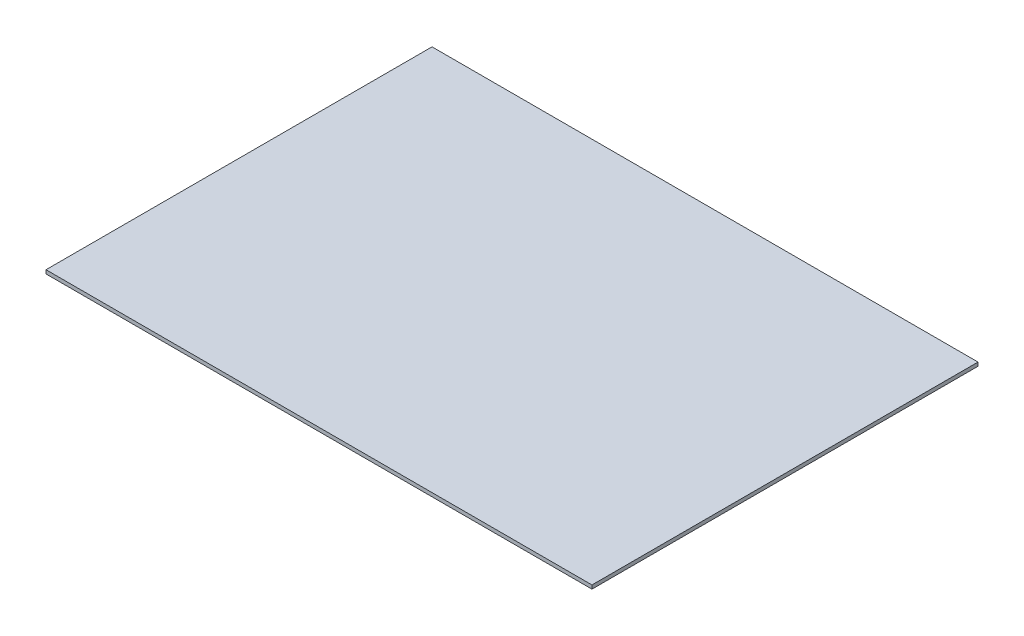
SolidWorks part; units mm, degrees
ref_plane "Plan de face" through (0, 0, 0) normal (0, 0, 1) x (1, 0, 0)
ref_plane "Plan de dessus" through (0, 0, 0) normal (0, 1, 0) x (1, 0, 0)
ref_plane "Plan de droite" through (0, 0, 0) normal (1, 0, 0) x (0, 0, -1)
sketch "Esquisse1" plane through (0, 0, 0) normal (0, 1, 0) x (1, 0, 0)
  line L1 (0, 0) -> (-297, 0)
  line L2 (0, 0) -> (0, 210)
  line L3 (0, 210) -> (-297, 210)
  line L4 (-297, 0) -> (-297, 210)
  dimension "D1" = 297
  dimension "D2" = 210
extrude "Boss.-Extru.1" add sketch "Esquisse1" along normal blind 2
